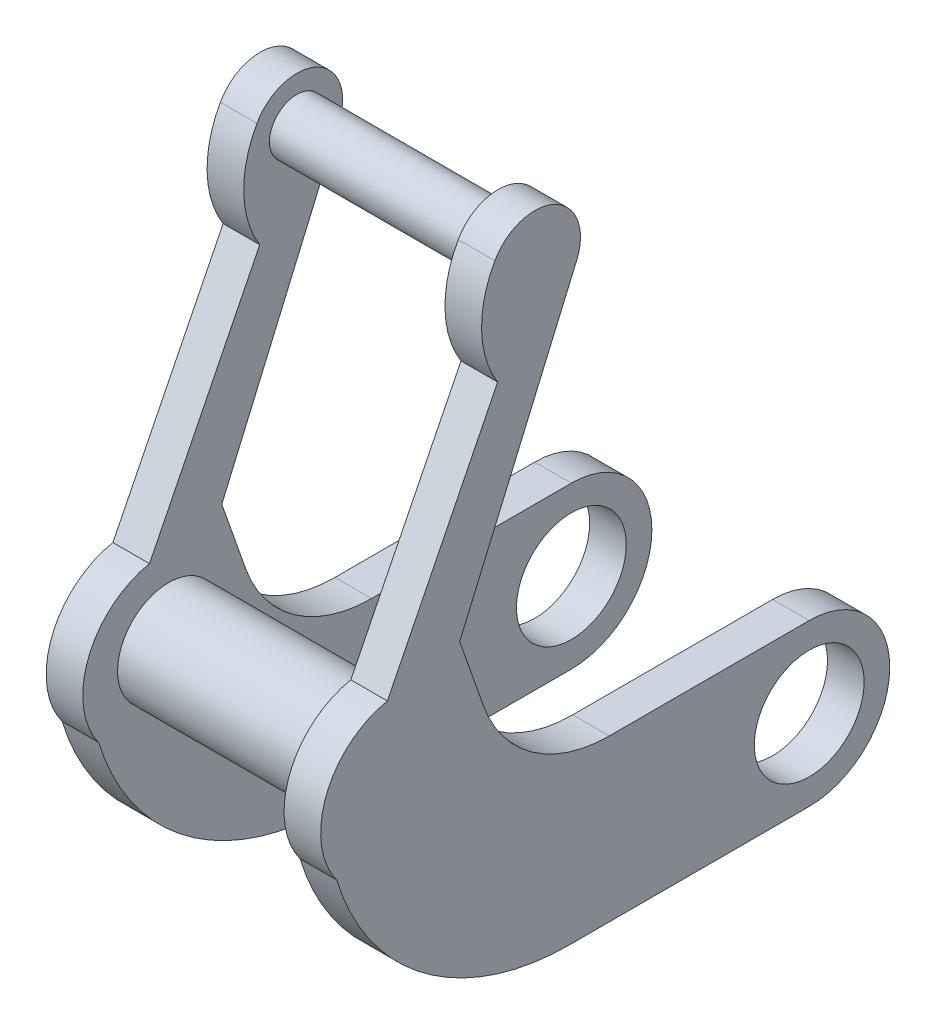
SolidWorks part; units mm, degrees
material "Chrome Stainless Steel"
ref_plane "Plano frontal" through (0, 0, 0) normal (0, 0, 1) x (1, 0, 0)
ref_plane "Plano superior" through (0, 0, 0) normal (0, 1, 0) x (1, 0, 0)
ref_plane "Plano direito" through (0, 0, 0) normal (1, 0, 0) x (0, 0, -1)
sketch "Sketch1" plane through (0, 0, 0) normal (1, 0, 0) x (0, 0, -1)
  line L0 (0, -44) -> (-131, -44)
  line L1 (0, 44) -> (-109.2151, 44)
  line L2 (-178.0704, 92.7522) -> (-191.0247, 129.5379)
  line L3 (-191.0247, 129.5379) -> (-127.0388, 278.1114)
  line L4 (-230.5315, 121.1839) -> (-170.2948, 242)
  circle A0 centre (0, 0) radius 30
  arc A1 (0, -44) -> (0, 44) centre (0, 0) ccw
  arc A2 (-230.5315, 121.1839) -> (-258.2606, 50.351) centre (-222, 77) ccw
  arc A3 (-258.2606, 50.351) -> (-131, -44) centre (-131, 89) ccw
  arc A4 (-178.0704, 92.7522) -> (-109.2151, 44) centre (-109.2151, 117) ccw
  arc A5 (-127.0388, 278.1114) -> (-171.8214, 300.1994) centre (-150, 288) ccw
  arc A6 (-171.8214, 300.1994) -> (-170.2948, 242) centre (-122.0686, 272.3848) ccw
  dimension "D1" = 60
  dimension "D2" = 88
  dimension "D5" = 133
  dimension "D6" = 77
  dimension "D7" = 73
  dimension "D11" = 50
  dimension "D12" = 150
  dimension "D3" = 45
  dimension "D17" = 57
  dimension "D4" = 222
  dimension "D8" = 39
  dimension "D9" = 137.3
  dimension "D10" = 66.7
  dimension "D13" = 288
  dimension "D14" = 131
  dimension "D15" = 3.2
  dimension "D16" = 135
  dimension "D18" = 242
extrude "Boss-Extrude1" add sketch "Sketch1" along normal blind 20
ref_plane "Plane1" through (-55, 0, 0) normal (1, 0, 0) x (0, 0, -1)
mirror "Mirror2" about plane through (-55, 0, 0) normal (1, 0, 0) of bodies 101
sketch "Sketch2" plane through (-55, 0, 0) normal (1, 0, 0) x (0, 0, -1)
  circle A0 centre (-150, 288) radius 15
  dimension "D1" = 30
extrude "Boss-Extrude2" add sketch "Sketch2" along normal mid plane 110
sketch "Sketch3" plane through (-55, 0, 0) normal (1, 0, 0) x (0, 0, -1)
  circle A0 centre (-220, 79) radius 28
  dimension "D3" = 56
  dimension "D1" = 79
  dimension "D2" = 220
extrude "Boss-Extrude3" add sketch "Sketch3" along normal mid plane 110
